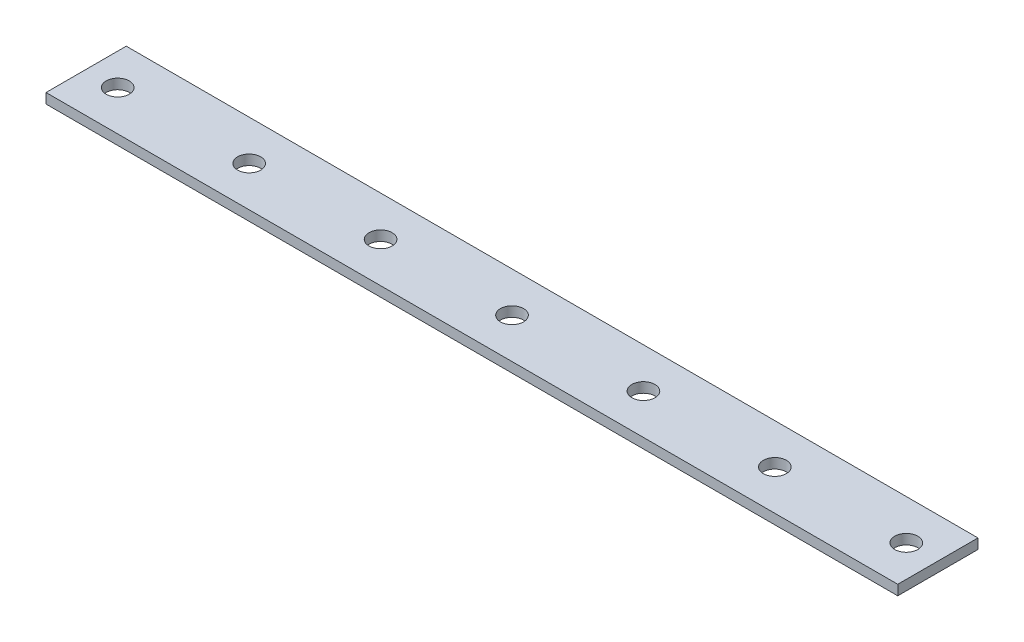
SolidWorks part; units mm, degrees
ref_plane "Front Plane" through (0, 0, 0) normal (0, 0, 1) x (1, 0, 0)
ref_plane "Top Plane" through (0, 0, 0) normal (0, 1, 0) x (1, 0, 0)
ref_plane "Right Plane" through (0, 0, 0) normal (1, 0, 0) x (0, 0, -1)
sketch "Sketch1" plane through (0, 0, 0) normal (0, 1, 0) x (1, 0, 0)
  line L0 (6, 6.35) -> (1, 6.35) construction
  line L1 (1, 0) -> (135.8, 0)
  line L2 (1, 0) -> (1, 12.7)
  line L3 (1, 12.7) -> (135.8, 12.7)
  line L4 (135.8, 0) -> (135.8, 12.7)
  line L5 (130.8, 6.35) -> (135.8, 6.35) construction
  circle A0 centre (6, 6.35) radius 1.8288
  circle A4 centre (130.8, 6.35) radius 1.3526 construction
  circle A5 centre (6, 6.35) radius 1.3526 construction
  circle A6 centre (130.8, 6.35) radius 1.8288
  point P11 (-0.8174, 6.35)
  dimension "D1" = 5
  dimension "D3" = 3.6576
  dimension "D2" = 12.7
extrude "Boss-Extrude1" add sketch "Sketch1" along normal blind 1.5875
sketch "Sketch2" plane through (0, 1.5875, 0) normal (0, 1, 0) x (1, 0, 0)
  line L0 (6, 6.35) -> (26.8, 6.35) construction
  line L1 (26.8, 6.35) -> (47.6, 6.35) construction
  line L2 (47.6, 6.35) -> (68.4, 6.35) construction
  line L3 (68.4, 6.35) -> (89.2, 6.35) construction
  line L4 (89.2, 6.35) -> (110, 6.35) construction
  line L5 (110, 6.35) -> (130.8, 6.35) construction
  circle A0 centre (26.8, 6.35) radius 1.8288
  circle A2 centre (47.6, 6.35) radius 1.8288
  circle A3 centre (68.4, 6.35) radius 1.8288
  circle A4 centre (89.2, 6.35) radius 1.8288
  circle A5 centre (110, 6.35) radius 1.8288
  circle A6 centre (6, 6.35) radius 1.8288 construction
extrude "Cut-Extrude1" cut sketch "Sketch2" against normal through all
